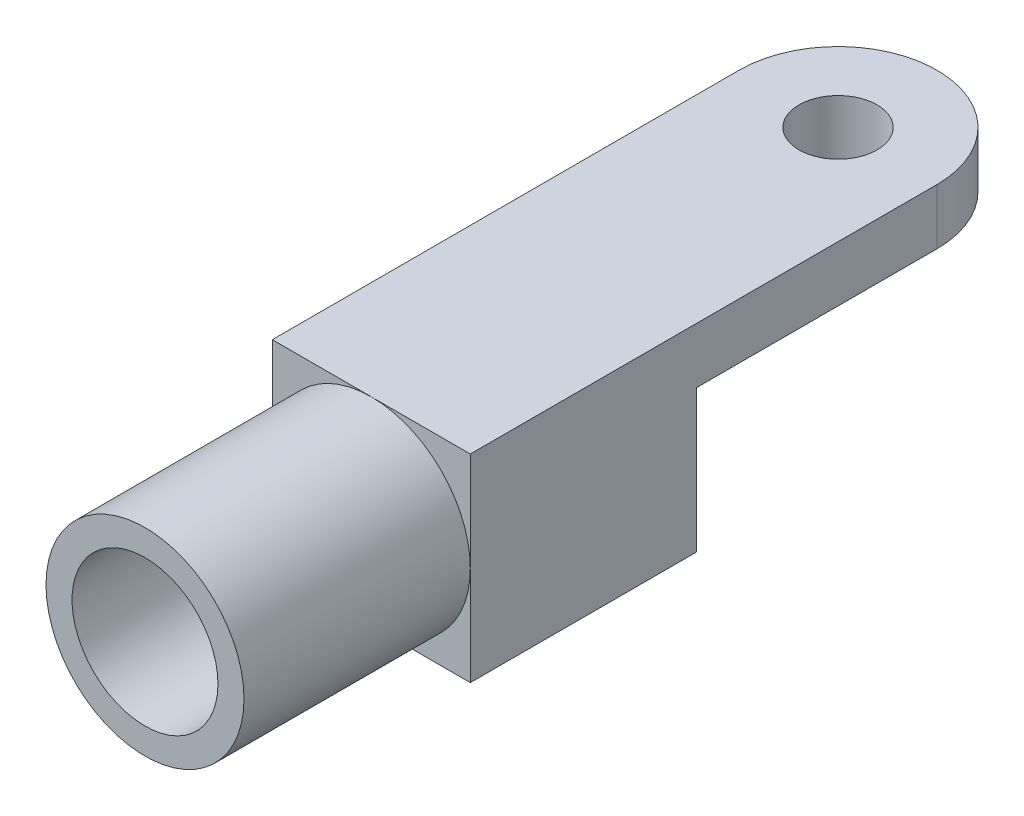
SolidWorks part; units mm, degrees
ref_plane "Front Plane" through (0, 0, 0) normal (0, 0, 1) x (1, 0, 0)
ref_plane "Top Plane" through (0, 0, 0) normal (0, 1, 0) x (1, 0, 0)
ref_plane "Right Plane" through (0, 0, 0) normal (1, 0, 0) x (0, 0, -1)
sketch "Sketch1" plane through (0, 0, 0) normal (0, 0, 1) x (1, 0, 0)
  circle A0 centre (0, 0) radius 3.275
  circle A1 centre (0, 0) radius 4.445
  dimension "D1" = 6.55
  dimension "D2" = 8.89
extrude "Boss-Extrude1" add sketch "Sketch1" along normal blind 10.16
sketch "Sketch2" plane through (0, 0, 0) normal (0, 0, -1) x (-1, 0, 0)
  line L1 (-4.445, 4.445) -> (4.445, 4.445)
  line L2 (-4.445, 4.445) -> (-4.445, -4.445)
  line L3 (-4.445, -4.445) -> (4.445, -4.445)
  line L4 (4.445, 4.445) -> (4.445, -4.445)
  circle A1 centre (0, 0) radius 4.445 construction
extrude "Boss-Extrude2" add sketch "Sketch2" along normal blind 25.4
sketch "Sketch3" plane through (0, -4.445, 0) normal (0, -1, 0) x (1, 0, 0)
  line L0 (4.445, -25.4) -> (-4.445, -25.4) construction
  line L1 (4.445, -25.4) -> (4.445, 0) construction
  line L2 (-4.445, -25.4) -> (-4.445, 0) construction
  line L3 (-4.445, -20.955) -> (-4.445, -25.4)
  line L4 (-4.445, -25.4) -> (4.445, -25.4)
  line L5 (4.445, -25.4) -> (4.445, -20.955)
  line L6 (4.445, -20.955) -> (-4.445, -20.955)
  circle A0 centre (0, -20.955) radius 4.445
  circle A1 centre (0, -20.955) radius 1.7526
  line M3 (-4.445, 0) -> (-4.445, -25.4)
  line M4 (-4.445, -25.4) -> (4.445, -25.4)
  line M5 (4.445, -25.4) -> (4.445, 0)
  dimension "D1" = 3.5052
extrude "Cut-Extrude1" cut sketch "Sketch3" against normal through all contours A0 L4 M5 | A0 M3 M4 | L6 A1 | L6 A1
sketch "Sketch4" plane through (-4.445, 0, 0) normal (-1, 0, 0) x (0, 0, 1)
  line L0 (-20.955, -4.445) -> (0, -4.445) construction
  line L1 (-10.16, -4.445) -> (-25.4, -4.445)
  line L2 (-10.16, -4.445) -> (-10.16, 1.9456)
  line L3 (-10.16, 1.9456) -> (-25.4, 1.9456)
  line L4 (-25.4, -4.445) -> (-25.4, 1.9456)
  line L5 (-25.4, 4.445) -> (-25.4, -4.445) construction
  line L9 (-17.78, -4.445) -> (-17.78, 1.9456) construction
  dimension "D1" = 15.24
  dimension "D2" = 6.3906
extrude "Cut-Extrude2" cut sketch "Sketch4" against normal through all
sketch "Sketch5" plane through (0, 4.445, 0) normal (0, 1, 0) x (1, 0, 0)
  line L0 (0, 25.4) -> (0, 0)
  arc A0 (4.445, 20.955) -> (-4.445, 20.955) centre (0, 20.955) ccw construction
